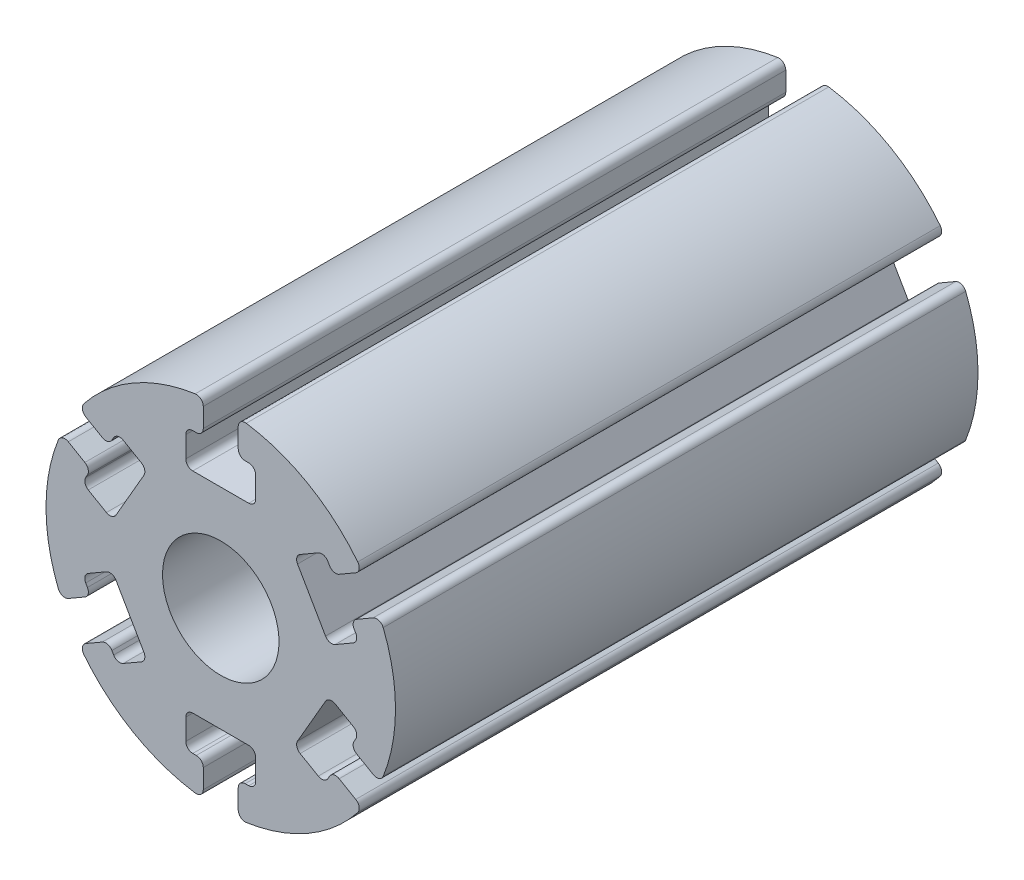
SolidWorks part; units mm, degrees
other "Marcação1"
sketch "Esboço6" plane through (-5, 5.7735, 12.5) normal (-0.9372, 0.3304, 0.1115) x (0.1181, 0, 0.993)
ref_plane "Plano frontal" through (0, 0, 0) normal (0, 0, 1) x (1, 0, 0)
ref_plane "Plano superior" through (0, 0, 0) normal (0, 1, 0) x (1, 0, 0)
ref_plane "Plano direito" through (0, 0, 0) normal (1, 0, 0) x (0, 0, -1)
sketch "Esboço1" plane through (0, 0, 0) normal (0, 0, 1) x (1, 0, 0)
  circle A0 centre (0, 0) radius 2.5 construction
  circle A2 centre (0, 0) radius 7.5
  dimension "D1" = 5
  dimension "D2" = 15
extrude "Ressalto-extrusão1" add sketch "Esboço1" along normal mid plane 25
sketch "Esboço7" plane through (0, 0, 12.5) normal (0, 0, -1) x (-1, 0, 0)
  circle A0 centre (0, 0) radius 2.5
  dimension "D1" = 5
extrude "Corte-extrusão1" cut sketch "Esboço7" along normal blind 16
sketch "Esboço9" plane through (0, 0, 12.5) normal (0, 0, 1) x (1, 0, 0)
  line L0 (-0.75, 6) -> (-0.75, 7.5)
  line L1 (-0.75, 7.5) -> (0.75, 7.5)
  line L2 (-1.5, 6) -> (-0.75, 6)
  line L3 (-1.5, 6) -> (-1.5, 4.5)
  line L4 (-1.5, 4.5) -> (1.5, 4.5)
  line L5 (1.5, 6) -> (1.5, 4.5)
  line L6 (0.75, 6) -> (1.5, 6)
  line L7 (0.75, 6) -> (0.75, 7.5)
  line L8 (4.4462, 4.299) -> (3.1471, 3.549)
  line L9 (4.4462, 4.299) -> (4.8212, 3.6495)
  line L10 (4.8212, 3.6495) -> (6.1202, 4.3995)
  line L11 (6.1202, 4.3995) -> (6.8702, 3.1005)
  line L12 (5.5712, 2.3505) -> (6.8702, 3.1005)
  line L13 (5.5712, 2.3505) -> (5.9462, 1.701)
  line L14 (5.9462, 1.701) -> (4.6471, 0.951)
  line L15 (3.1471, 3.549) -> (4.6471, 0.951)
  line L16 (5.9462, -1.701) -> (4.6471, -0.951)
  line L17 (5.9462, -1.701) -> (5.5712, -2.3505)
  line L18 (5.5712, -2.3505) -> (6.8702, -3.1005)
  line L19 (6.8702, -3.1005) -> (6.1202, -4.3995)
  line L20 (4.8212, -3.6495) -> (6.1202, -4.3995)
  line L21 (4.8212, -3.6495) -> (4.4462, -4.299)
  line L22 (4.4462, -4.299) -> (3.1471, -3.549)
  line L23 (4.6471, -0.951) -> (3.1471, -3.549)
  line L24 (1.5, -6) -> (1.5, -4.5)
  line L25 (1.5, -6) -> (0.75, -6)
  line L26 (0.75, -6) -> (0.75, -7.5)
  line L27 (0.75, -7.5) -> (-0.75, -7.5)
  line L28 (-0.75, -6) -> (-0.75, -7.5)
  line L29 (-0.75, -6) -> (-1.5, -6)
  line L30 (-1.5, -6) -> (-1.5, -4.5)
  line L31 (1.5, -4.5) -> (-1.5, -4.5)
  line L32 (-4.4462, -4.299) -> (-3.1471, -3.549)
  line L33 (-4.4462, -4.299) -> (-4.8212, -3.6495)
  line L34 (-4.8212, -3.6495) -> (-6.1202, -4.3995)
  line L35 (-6.1202, -4.3995) -> (-6.8702, -3.1005)
  line L36 (-5.5712, -2.3505) -> (-6.8702, -3.1005)
  line L37 (-5.5712, -2.3505) -> (-5.9462, -1.701)
  line L38 (-5.9462, -1.701) -> (-4.6471, -0.951)
  line L39 (-3.1471, -3.549) -> (-4.6471, -0.951)
  line L40 (-5.9462, 1.701) -> (-4.6471, 0.951)
  line L41 (-5.9462, 1.701) -> (-5.5712, 2.3505)
  line L42 (-5.5712, 2.3505) -> (-6.8702, 3.1005)
  line L43 (-6.8702, 3.1005) -> (-6.1202, 4.3995)
  line L44 (-4.8212, 3.6495) -> (-6.1202, 4.3995)
  line L45 (-4.8212, 3.6495) -> (-4.4462, 4.299)
  line L46 (-4.4462, 4.299) -> (-3.1471, 3.549)
  line L47 (-4.6471, 0.951) -> (-3.1471, 3.549)
  circle A0 centre (0, 0) radius 7.5 construction
  point P7 (0, 7.5)
  point P55 (0, 0)
  dimension "D1" = 1.5
  dimension "D2" = 3
  dimension "D3" = 3
  dimension "D4" = 1.5
  dimension "D5" = 6
extrude "Corte-extrusão2" cut sketch "Esboço9" against normal through all
fillet "Filete2" radius 0.3 48 edges at (0.75, 7.4624, 0) (6.0876, 4.3807, 0) (4.8212, 3.6495, 0) (4.4462, 4.299, 0) (3.1471, 3.549, 0) (4.6471, 0.951, 0) (5.9462, 1.701, 0) (5.5712, 2.3505, 0) (6.8376, 3.0817, 0) (6.8376, -3.0817, 0) (5.5712, -2.3505, 0) (5.9462, -1.701, 0) (4.6471, -0.951, 0) (3.1471, -3.549, 0) (4.4462, -4.299, 0) (4.8212, -3.6495, 0) (6.0876, -4.3807, 0) (0.75, -7.4624, 0) (0.75, -6, 0) (1.5, -6, 0) (1.5, -4.5, 0) (-1.5, -4.5, 0) (-1.5, -6, 0) (-0.75, -6, 0) (-0.75, -7.4624, 0) (-6.0876, -4.3807, 0) (-4.8212, -3.6495, 0) (-4.4462, -4.299, 0) (-3.1471, -3.549, 0) (-4.6471, -0.951, 0) (-5.9462, -1.701, 0) (-5.5712, -2.3505, 0) (-6.8376, -3.0817, 0) (-6.8376, 3.0817, 0) (-5.5712, 2.3505, 0) (-5.9462, 1.701, 0) (-4.6471, 0.951, 0) (-3.1471, 3.549, 0) (-4.4462, 4.299, 0) (-4.8212, 3.6495, 0) (-6.0876, 4.3807, 0) (-0.75, 7.4624, 0) (-0.75, 6, 0) (-1.5, 6, 0) (1.5, 6, 0) (0.75, 6, 0) (1.5, 4.5, 0) (-1.5, 4.5, 0)
move or copy body "Corpo-Converter em corpo de malha1" [suppressed] bodies to move or copy 105 copy no translate (0, 0, 0) parameters "D1"=0, "D2"=0, "D3"=0
